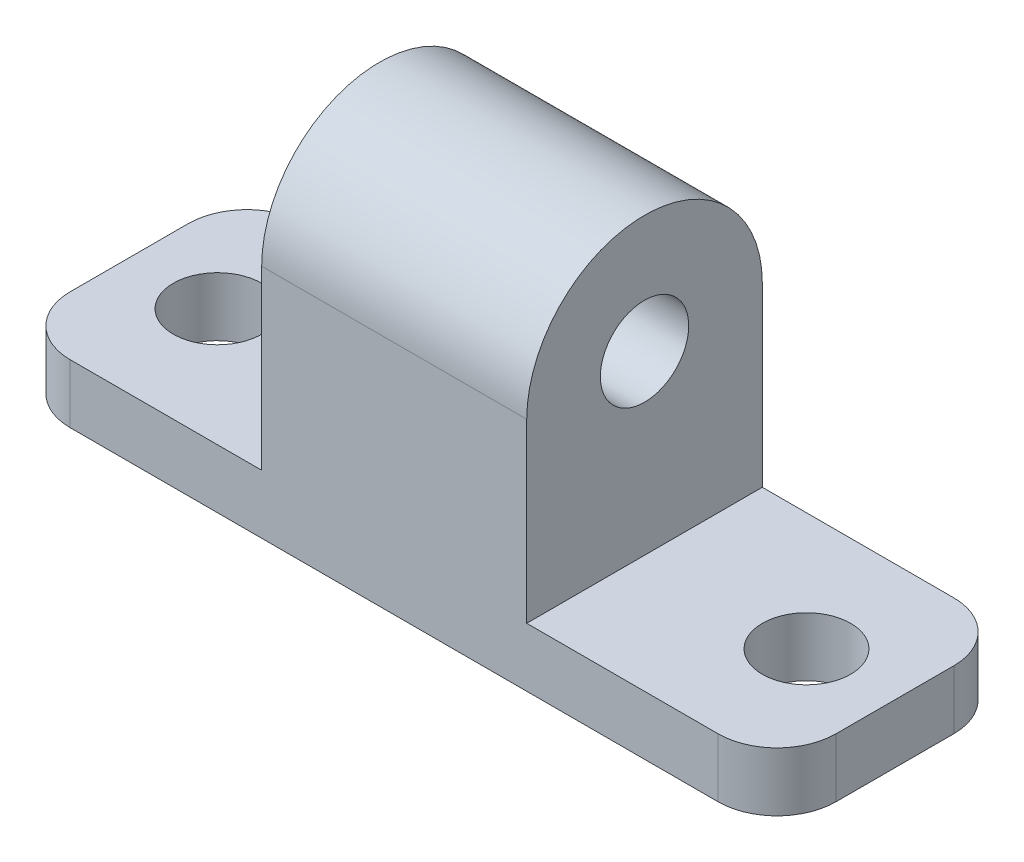
SolidWorks part; units mm, degrees
ref_plane "Front" through (0, 0, 0) normal (0, 0, 1) x (1, 0, 0)
ref_plane "Top" through (0, 0, 0) normal (0, 1, 0) x (1, 0, 0)
ref_plane "Right" through (0, 0, 0) normal (1, 0, 0) x (0, 0, -1)
sketch "Sketch1" plane through (0, 0, 0) normal (0, 0, 1) x (1, 0, 0)
  line L1 (-13, 6) -> (13, 6)
  line L2 (-13, 6) -> (-13, -6)
  line L3 (-13, -6) -> (13, -6)
  line L4 (13, 6) -> (13, -6)
  line L5 (-13, 6) -> (13, -6) construction
  line L6 (-13, -6) -> (13, 6) construction
  point P0 (0, 0)
  dimension "D1" = 26
  dimension "D2" = 12
extrude "Boss-Extrude1" add sketch "Sketch1" along normal blind 8
sketch "Sketch2" plane through (13, 0, 0) normal (1, 0, 0) x (0, 0, -1)
  line L0 (-8, 6) -> (0, 6) construction
  line L1 (0, -6) -> (0, 6) construction
  line L3 (-8, 2) -> (-8, 7)
  line L4 (-8, 7) -> (0, 7)
  line L5 (0, 7) -> (0, 2)
  line L6 (-8, -6) -> (-8, 6) construction
  arc A0 (0, 2) -> (-8, 2) centre (-4, 2) ccw
  dimension "D1" = 1
extrude "Cut-Extrude1" cut sketch "Sketch2" against normal through all
sketch "Sketch3" plane through (0, 0, 8) normal (0, 0, 1) x (1, 0, 0)
  line L0 (13, 6) -> (-13, 6) construction
  line L5 (13, -6) -> (13, 2) construction
  line L6 (4.5, 6) -> (13, 6)
  line L7 (4.5, 6) -> (4.5, -4)
  line L8 (4.5, -4) -> (13, -4)
  line L9 (13, 6) -> (13, -4)
  line L10 (-13, 2) -> (-13, -6) construction
  line L11 (-4.5, 6) -> (-13, 6)
  line L12 (-4.5, 6) -> (-4.5, -4)
  line L13 (-4.5, -4) -> (-13, -4)
  line L14 (-13, 6) -> (-13, -4)
  line L17 (-13, -6) -> (13, -6) construction
  dimension "D1" = 9
  dimension "D2" = 2
extrude "Cut-Extrude2" cut sketch "Sketch3" against normal through all
sketch "Sketch4" plane through (4.5, 0, 0) normal (1, 0, 0) x (0, 0, -1)
  circle A0 centre (-4, 2) radius 1.5
  dimension "D1" = 3
extrude "Cut-Extrude3" cut sketch "Sketch4" against normal through all
fillet "Fillet1" radius 2 4 edges at (-13, -5, 0) (-13, -5, 8) (13, -5, 0) (13, -5, 8)
sketch "Sketch5" plane through (0, -4, 0) normal (0, 1, 0) x (1, 0, 0)
  line L0 (-13, -4) -> (-10, -4) construction
  line L1 (-13, -2) -> (-13, -6) construction
  line L2 (10, -4) -> (13, -4) construction
  line L6 (13, -2) -> (13, -6) construction
  circle A0 centre (-10, -4) radius 1.5
  circle A1 centre (10, -4) radius 1.5
  dimension "D2" = 3
  dimension "D1" = 3
extrude "Cut-Extrude4" cut sketch "Sketch5" against normal through all
